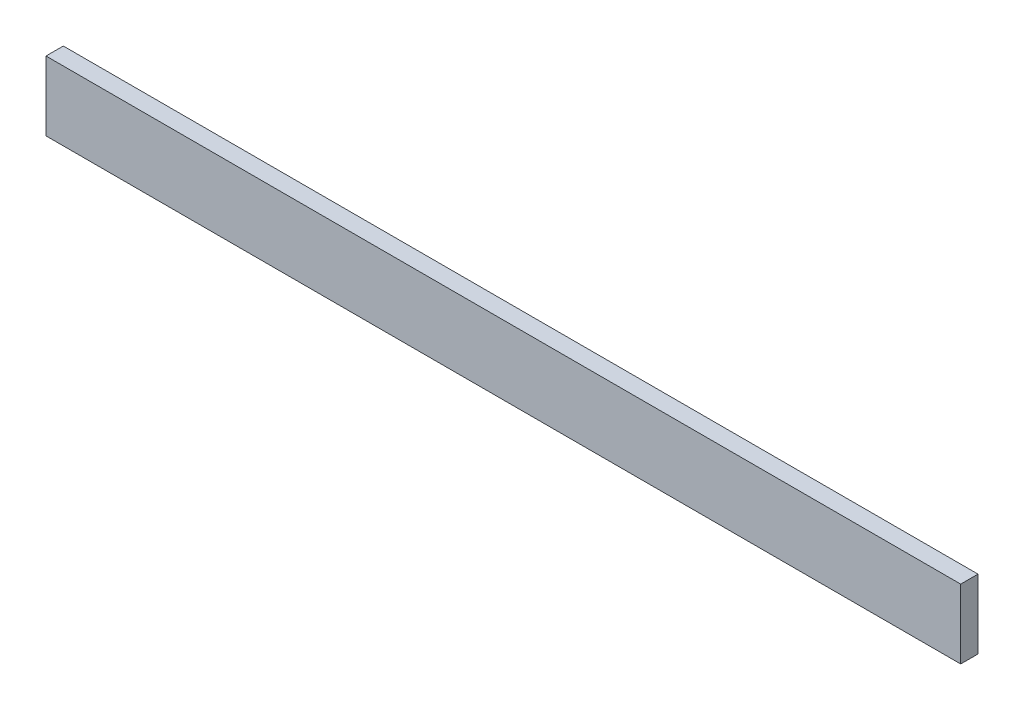
SolidWorks part; units mm, degrees
ref_plane "Front Plane" through (0, 0, 0) normal (0, 0, 1) x (1, 0, 0)
ref_plane "Top Plane" through (0, 0, 0) normal (0, 1, 0) x (1, 0, 0)
ref_plane "Right Plane" through (0, 0, 0) normal (1, 0, 0) x (0, 0, -1)
sketch "Sketch1" plane through (0, 0, 0) normal (0, 0, 1) x (1, 0, 0)
  line L1 (335.7562, 25.4) -> (-335.7562, 25.4)
  line L2 (335.7562, 25.4) -> (335.7562, -25.4)
  line L3 (335.7562, -25.4) -> (-335.7562, -25.4)
  line L4 (-335.7562, 25.4) -> (-335.7562, -25.4)
  line L5 (335.7562, 25.4) -> (-335.7562, -25.4) construction
  line L6 (335.7562, -25.4) -> (-335.7562, 25.4) construction
  point P0 (0, 0)
  dimension "D1" = 50.8
  dimension "D2" = 671.5125
extrude "Boss-Extrude1" add sketch "Sketch1" along normal blind 12.7
